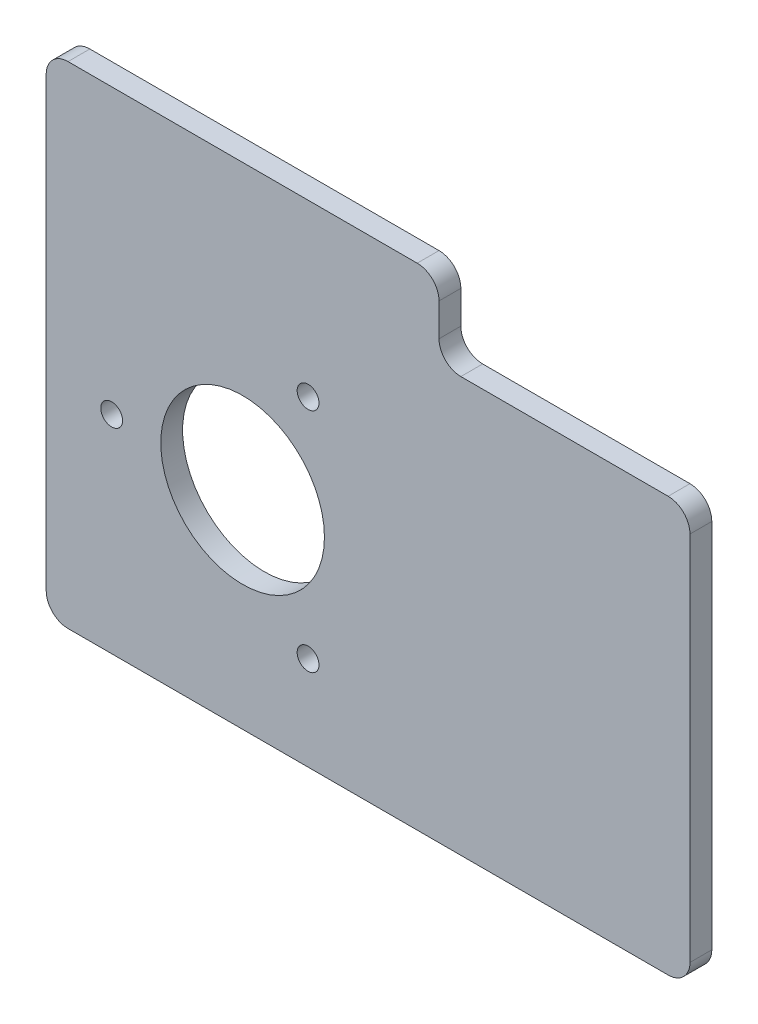
SolidWorks part; units mm, degrees
other "FrameSub(PCB)"
material "Epoxy, Unfilled"
ref_plane "Front" through (0, 0, 0) normal (0, 0, 1) x (1, 0, 0)
ref_plane "Top" through (0, 0, 0) normal (0, 1, 0) x (1, 0, 0)
ref_plane "Right" through (0, 0, 0) normal (1, 0, 0) x (0, 0, -1)
sketch "BoardSke" plane through (0, 0, 0) normal (0, 0, 1) x (1, 0, 0)
  line L0 (9, 13) -> (9, 9.5)
  line L1 (-9, 13) -> (20.5, 13) construction
  line L2 (-9, 13) -> (-9, -13) construction
  line L3 (-9, -13) -> (20.5, -13) construction
  line L4 (20.5, 13) -> (20.5, -13) construction
  line L5 (-9, 13) -> (20.5, -13) construction
  line L6 (-9, -13) -> (20.5, 13) construction
  line L7 (6, 7) -> (18, 7) construction
  line L8 (6, 7) -> (6, -7) construction
  line L9 (6, -7) -> (18, -7) construction
  line L10 (18, 7) -> (18, -7) construction
  line L11 (6, 7) -> (18, -7) construction
  line L12 (6, -7) -> (18, 7) construction
  line L13 (-7.75, 12) -> (7.75, 12) construction
  line L14 (-7.75, 12) -> (-7.75, 7) construction
  line L15 (-7.75, 7) -> (7.75, 7) construction
  line L16 (7.75, 12) -> (7.75, 7) construction
  line L17 (-7.75, 12) -> (7.75, 7) construction
  line L18 (-7.75, 7) -> (7.75, 12) construction
  line L19 (9, 9.5) -> (20.5, 9.5)
  line L20 (50, 0) -> (-50, 0) construction
  line L23 (-9, 13) -> (9, 13)
  line L24 (20.5, 9.5) -> (20.5, -9.5)
  line L26 (-9, 13) -> (-9, -9.5)
  line L27 (-9, -9.5) -> (20.5, -9.5)
  circle A0 centre (0, 0) radius 8 construction
  circle A1 centre (-6, 0) radius 0.5
  circle A2 centre (0, 0) radius 3.75
  circle A3 centre (3, 5.1962) radius 0.5
  circle A4 centre (3, -5.1962) radius 0.5
  point P7 (12, 0)
  point P8 (5.75, 0)
  point P13 (0, 0)
  point P26 (0, 9.5)
  dimension "D1" = 16
  dimension "D2" = 1
  dimension "D4" = 7.5
  dimension "D3" = 6
  dimension "D6" = 12
  dimension "D7" = 14
  dimension "D8" = 12
  dimension "D9" = 26
  dimension "D10" = 2.5
  dimension "D11" = 9
  dimension "D12" = 15.5
  dimension "D13" = 5
  dimension "D14" = 2.5
  dimension "D15" = 9.5
  dimension "D16" = 1.25
  dimension "D17" = 1.25
  dimension "D18" = 3
  dimension "D5" = 3
extrude "Board" add sketch "BoardSke" along normal blind 1
fillet "Fillet" radius 1 6 edges at (20.5, 9.5, 0.5) (9, 9.5, 0.5) (9, 13, 0.5) (20.5, -9.5, 0.5) (-9, -9.5, 0.5) (-9, 13, 0.5)
